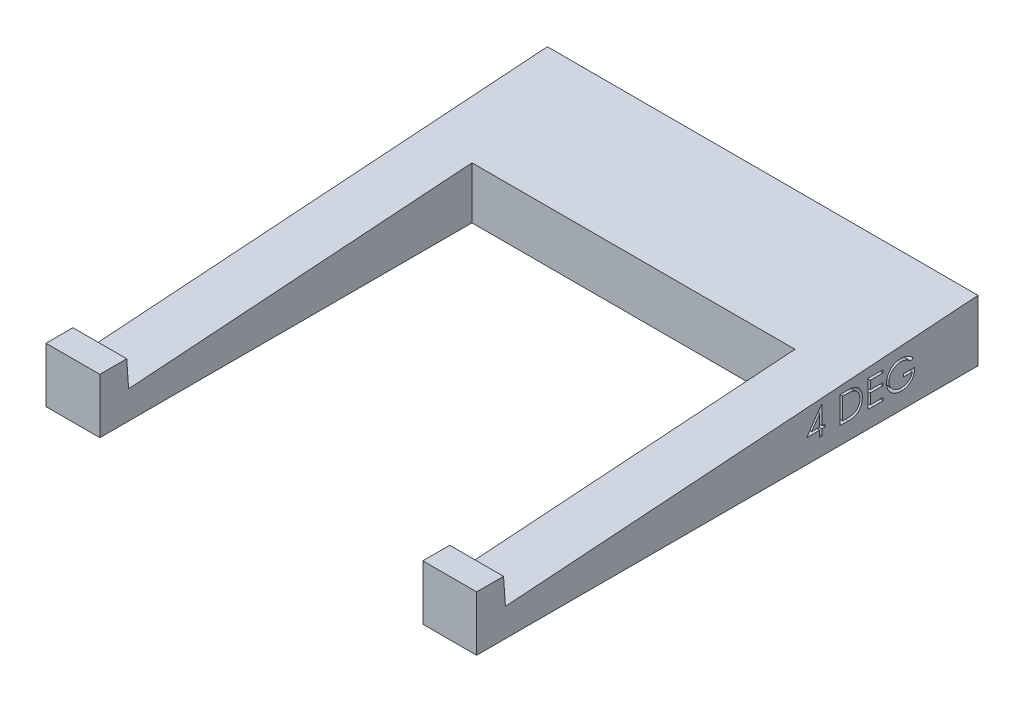
SolidWorks part; units mm, degrees
ref_plane "Front Plane" through (0, 0, 0) normal (0, 0, 1) x (1, 0, 0)
ref_plane "Top Plane" through (0, 0, 0) normal (0, 1, 0) x (1, 0, 0)
ref_plane "Right Plane" through (0, 0, 0) normal (1, 0, 0) x (0, 0, -1)
sketch "Sketch1" plane through (0, 0, 0) normal (1, 0, 0) x (0, 0, -1)
  line L1 (11.9888, 15.748) -> (11.9888, 22.948)
  line L2 (11.9888, 22.948) -> (6.9212, 22.5936)
  line L4 (0, 19.05) -> (11.9888, 19.05) construction
  line L5 (6.9212, 22.5936) -> (-43.7551, 19.05) construction
  line L6 (-43.7551, 19.05) -> (0, 19.05) construction
  line L7 (-43.7551, 19.05) -> (6.9212, 22.5936)
  line L8 (-43.7551, 19.05) -> (-43.9771, 22.225)
  line L9 (-43.9771, 22.225) -> (-47.1521, 22.225)
  line L10 (-47.1521, 22.225) -> (-47.1521, 15.748)
  line L11 (-47.1521, 15.748) -> (11.9888, 15.748)
  dimension "D1" = 4
  dimension "D2" = 11.9888
  dimension "D3" = 55.88
  dimension "D4" = 15.748
  dimension "D5" = 3.175
  dimension "D6" = 3.175
  dimension "D7" = 3.302
  dimension "D8" = 50.8
  dimension "D9" = 11.9888
extrude "Boss-Extrude1" add sketch "Sketch1" along normal blind 50.8
sketch "Sketch2" [suppressed] plane through (0, 0, 0) normal (0, 0, 1) x (1, 0, 0)
  line L0 (50.8, 0) -> (0, 0) construction
  line L1 (19.05, 19.05) -> (31.75, 19.05)
  line L2 (19.05, 19.05) -> (19.05, 0)
  line L3 (19.05, 0) -> (31.75, 0)
  line L4 (31.75, 19.05) -> (31.75, 0)
  line L5 (19.05, 19.05) -> (31.75, 0) construction
  line L6 (19.05, 0) -> (31.75, 19.05) construction
  line L8 (0, 0) -> (12.7, 0)
  line L9 (0, 0) -> (0, 19.05)
  line L10 (0, 19.05) -> (12.7, 19.05)
  line L11 (12.7, 0) -> (12.7, 19.05)
  line L12 (50.8, 0) -> (38.1, 0)
  line L13 (50.8, 0) -> (50.8, 19.05)
  line L14 (50.8, 19.05) -> (38.1, 19.05)
  line L15 (38.1, 0) -> (38.1, 19.05)
  point P0 (25.4, 9.525)
  point P7 (25.4, 0)
  dimension "D1" = 19.05
  dimension "D2" = 12.7
  dimension "D3" = 12.7
  dimension "D4" = 12.7
extrude "Cut-Extrude1" [suppressed] cut sketch "Sketch2" against normal through all
hole_wizard "M3 Clearance Hole1" [suppressed] positions "Sketch3" profile "Sketch4" hole size "M3" standard "ANSI Metric"
sketch "Sketch3" [suppressed] plane through (50.8, 0, 0) normal (1, 0, 0) x (0, 0, -1)
  line L0 (11.9888, 19.05) -> (0, 19.05) construction
  line L2 (11.9888, 19.05) -> (11.9888, 26.827) construction
  point P0 (5.9944, 13.0556)
  dimension "D1" = 5.9944
  dimension "D2" = 5.9944
sketch "Sketch4" plane through (50.8, 13.0556, -5.9944) normal (0, 1, 0) x (0, 0, -1)
  line L0 (0, 0) -> (0, 50.8)
  line L1 (0, 50.8) -> (1.8, 50.8)
  line L2 (1.8, 50.8) -> (1.8, 0)
  line L5 (1.8, 0) -> (0, 0)
  line L11 (0, -6.35) -> (0, 107.95) construction
  dimension "Thru Hole Dia." = 3.6
  dimension "Thru Hole Depth" = 50.8
sketch "Sketch5" plane through (0, 0, 0) normal (0, 1, 0) x (1, 0, 0)
  line L0 (50.8, -47.1521) -> (0, -47.1521) construction
  line L1 (44.45, -47.1521) -> (6.35, -47.1521)
  line L2 (44.45, -47.1521) -> (44.45, -3.2512)
  line L3 (44.45, -3.2512) -> (6.35, -3.2512)
  line L4 (6.35, -47.1521) -> (6.35, -3.2512)
  line L5 (0, -47.1521) -> (0, 11.9888) construction
  line L6 (50.8, 11.9888) -> (0, 11.9888) construction
  dimension "D1" = 38.1
  dimension "D2" = 6.35
  dimension "D3" = 15.24
extrude "Cut-Extrude2" cut sketch "Sketch5" along normal through all
sketch "Sketch7" plane through (50.8, 0, 0) normal (1, 0, 0) x (0, 0, -1)
  line L1 (-47.1521, 15.748) -> (11.9888, 15.748) construction
  line L2 (11.9888, 15.748) -> (11.9888, 22.948) construction
  text T0 "4 DEG"
  dimension "D1" = 2.032
  dimension "D2" = 20.32
extrude "Cut-Extrude4" cut sketch "Sketch7" against normal blind 2.54
